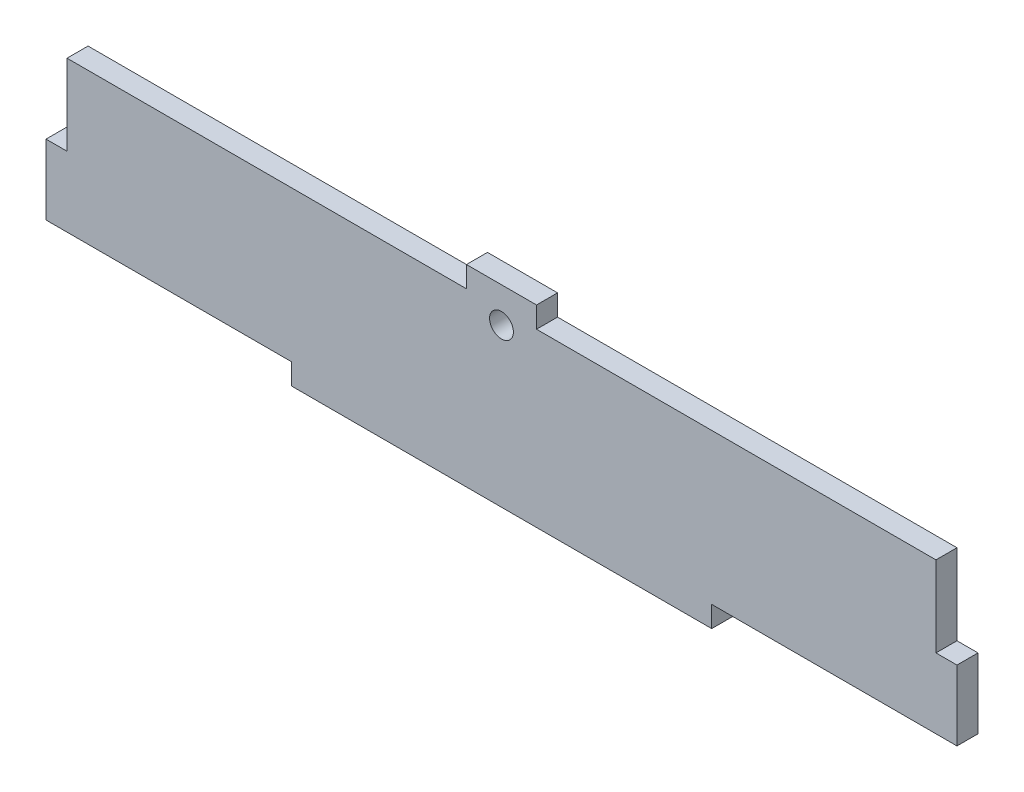
SolidWorks part; units mm, degrees
ref_plane "Front Plane" through (0, 0, 0) normal (0, 0, 1) x (1, 0, 0)
ref_plane "Top Plane" through (0, 0, 0) normal (0, 1, 0) x (1, 0, 0)
ref_plane "Right Plane" through (0, 0, 0) normal (1, 0, 0) x (0, 0, -1)
sketch "Sketch1" plane through (0, 0, 0) normal (0, 0, 1) x (1, 0, 0)
  line L0 (-130, 27.2992) -> (-130, -27.2992) construction
  line L1 (130, 49) -> (-130, 49)
  line L2 (130, 49) -> (130, 0)
  line L3 (130, 0) -> (-130, 0)
  line L4 (-130, 49) -> (-130, 0)
  line L5 (-124, 49) -> (-130, 49) construction
extrude "Boss-Extrude1" add sketch "Sketch1" along normal blind 6
sketch "Sketch2" plane through (0, 0, 0) normal (0, 0, -1) x (-1, 0, 0)
  line L0 (-130, 43) -> (130, 43) construction
  line L1 (-130, 49) -> (-10, 49)
  line L2 (-130, 49) -> (-130, 43)
  line L3 (-130, 43) -> (-10, 43)
  line L4 (-10, 49) -> (-10, 43)
  line L5 (10, 43) -> (130, 43)
  line L6 (10, 43) -> (10, 49)
  line L7 (10, 49) -> (130, 49)
  line L8 (130, 43) -> (130, 49)
  dimension "D1" = 10
  dimension "D2" = 10
extrude "Cut-Extrude1" cut sketch "Sketch2" against normal blind 6
hole_wizard "M8x1.25 Tapped Hole1" positions "Sketch3" profile "Sketch4" tap size "M8x1.25" standard "ANSI Metric"
sketch "Sketch3" plane through (0, 0, 0) normal (0, 0, -1) x (-1, 0, 0)
  point P0 (0, 39)
sketch "Sketch4" plane through (0, 39, 0) normal (1, 0, 0) x (0, 1, 0)
  line L0 (0, 0) -> (0, 6)
  line L1 (0, 6) -> (3.4, 6)
  line L2 (3.4, 6) -> (3.4, 0)
  line L5 (3.4, 0) -> (0, 0)
  line L11 (0, -6.35) -> (0, 107.95) construction
  dimension "Thread Major Dia." = 6.8
  dimension "Thru Tap Drill Depth" = 6
sketch "Sketch5" plane through (0, 0, 0) normal (0, 0, -1) x (-1, 0, 0)
  line L0 (-124, 20) -> (-124, 43) construction
  line L1 (-130, 43) -> (-124, 43)
  line L2 (-130, 43) -> (-130, 20)
  line L3 (-130, 20) -> (-124, 20)
  line L4 (-124, 43) -> (-124, 20)
  line L5 (124, 20) -> (130, 20) construction
  line L6 (130, 43) -> (124, 43)
  line L7 (130, 43) -> (130, 20)
  line L8 (130, 20) -> (124, 20)
  line L9 (124, 43) -> (124, 20)
  line L10 (130, 43) -> (130, 0) construction
  line L11 (130, 20) -> (130, 43) construction
  line L13 (124, 43) -> (130, 43) construction
extrude "Cut-Extrude2" cut sketch "Sketch5" against normal up to next
sketch "Sketch6" plane through (0, 0, 0) normal (0, 0, -1) x (-1, 0, 0)
  line L0 (-130, -6) -> (130, -6) construction
  line L1 (-60, 0) -> (60, 0)
  line L2 (-60, 0) -> (-60, -6)
  line L3 (-60, -6) -> (60, -6)
  line L4 (60, 0) -> (60, -6)
  point P4 (0, 0)
  dimension "D1" = 120
extrude "Boss-Extrude2" add sketch "Sketch6" against normal blind 6
